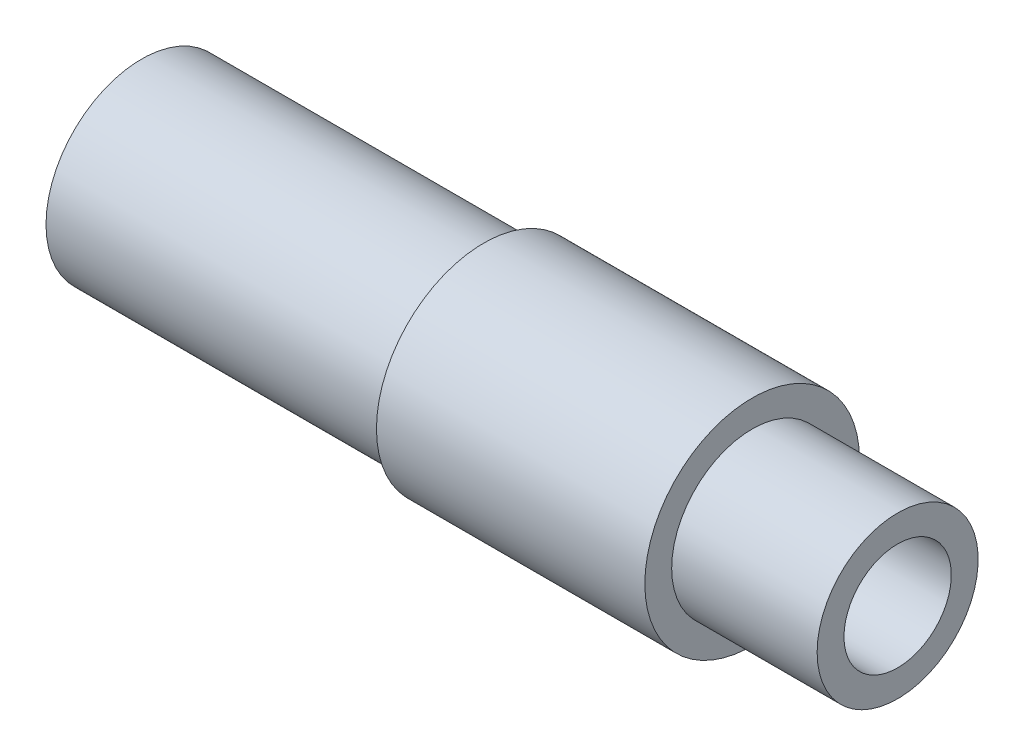
SolidWorks part; units mm, degrees
ref_plane "Front Plane" through (0, 0, 0) normal (0, 0, 1) x (1, 0, 0)
ref_plane "Top Plane" through (0, 0, 0) normal (0, 1, 0) x (1, 0, 0)
ref_plane "Right Plane" through (0, 0, 0) normal (1, 0, 0) x (0, 0, -1)
sketch "Sketch1" plane through (0, 0, 0) normal (0, 0, 1) x (1, 0, 0)
  line L0 (-83.6737, 19.6329) -> (88.7001, 19.6329) construction
  line L1 (-72.1427, 24.7579) -> (-44.6427, 24.7579)
  line L2 (-72.1427, 26.7579) -> (-46.6427, 26.7579)
  line L3 (-46.6427, 26.7579) -> (-46.6427, 27.6329)
  line L4 (-46.6427, 27.6329) -> (-26.6427, 27.6329)
  line L5 (-44.6427, 24.7579) -> (-44.6427, 25.6329)
  line L7 (-72.1427, 26.7579) -> (-72.1427, 24.7579)
  line L9 (-44.6427, 25.6329) -> (-26.6427, 25.6329) construction
  line L10 (-26.6427, 27.6329) -> (-26.6427, 25.6329)
  line L11 (-26.6427, 25.6329) -> (-15.8035, 25.6329)
  line L18 (-28.6427, 25.6329) -> (-28.6427, 23.6329)
  line L19 (-28.6427, 23.6329) -> (-15.8035, 23.6329)
  line L21 (-15.8035, 25.6329) -> (-15.8035, 23.6329)
  line L22 (-42.6427, 25.6329) -> (-28.6427, 25.6329) construction
  line L23 (-42.6427, 25.6329) -> (-42.6427, 25.6329) construction
  line L24 (-42.6427, 25.6329) -> (-42.6427, 25.6329) construction
  line L25 (-42.6427, 25.6329) -> (-42.6427, 25.6329) construction
  line L26 (-42.6427, 25.6329) -> (-42.6427, 25.6329) construction
  line L27 (-42.6427, 25.6329) -> (-42.6427, 25.6329) construction
  line L28 (-44.6427, 25.6329) -> (-28.6427, 25.6329)
  dimension "D2" = 14.25
  dimension "D3" = 25.5
  dimension "D4" = 20
  dimension "D5" = 16
  dimension "D7" = 12
  dimension "D1" = 2
  dimension "D6" = 2
revolve "Revolve1" add sketch "Sketch1" angle 360 about L0
